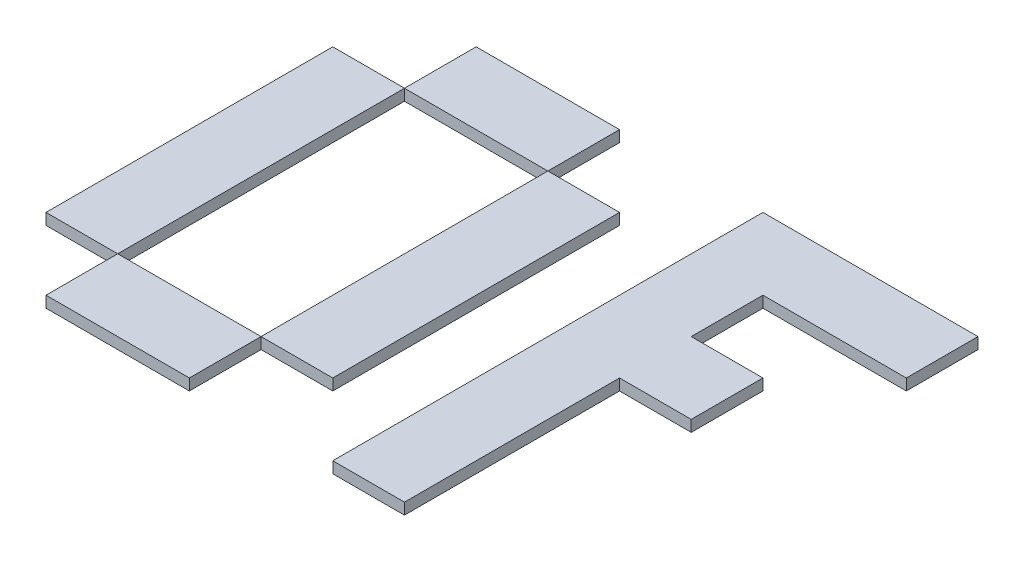
SolidWorks part; units mm, degrees
ref_plane "Front Plane" through (0, 0, 0) normal (0, 0, 1) x (1, 0, 0)
ref_plane "Top Plane" through (0, 0, 0) normal (0, 1, 0) x (1, 0, 0)
ref_plane "Right Plane" through (0, 0, 0) normal (1, 0, 0) x (0, 0, -1)
sketch "Sketch1" plane through (0, 0, 0) normal (0, 1, 0) x (1, 0, 0)
  line L1 (0, 0) -> (127, 0)
  line L2 (0, 0) -> (0, 203.2)
  line L3 (0, 203.2) -> (127, 203.2)
  line L4 (127, 0) -> (127, 203.2)
  dimension "D1" = 127
  dimension "D2" = 203.2
extrude "Boss-Extrude1" add sketch "Sketch1" along normal blind 2 contours L1 L4 L3 L2
sketch "Sketch2" plane through (0, 2, 0) normal (0, 1, 0) x (1, 0, 0)
  line L0 (0, 0) -> (0, 203.2) construction
  line L1 (12.7, 127) -> (25.4, 127)
  line L2 (12.7, 127) -> (12.7, 76.2)
  line L3 (12.7, 76.2) -> (25.4, 76.2)
  line L4 (25.4, 127) -> (25.4, 76.2)
  line L5 (0, 0) -> (127, 0) construction
  line L6 (88.9, 127) -> (88.9, 114.3)
  line L7 (25.4, 127) -> (50.8, 127)
  line L8 (25.4, 127) -> (25.4, 139.7)
  line L9 (25.4, 139.7) -> (50.8, 139.7)
  line L10 (50.8, 127) -> (50.8, 139.7)
  line L11 (25.4, 76.2) -> (50.8, 76.2)
  line L12 (25.4, 76.2) -> (25.4, 63.5)
  line L13 (25.4, 63.5) -> (50.8, 63.5)
  line L14 (50.8, 76.2) -> (50.8, 63.5)
  line L15 (50.8, 127) -> (63.5, 127)
  line L16 (50.8, 127) -> (50.8, 76.2)
  line L17 (50.8, 76.2) -> (63.5, 76.2)
  line L18 (63.5, 127) -> (63.5, 76.2)
  line L19 (76.2, 63.5) -> (88.9, 63.5)
  line L20 (76.2, 63.5) -> (76.2, 139.7)
  line L21 (76.2, 139.7) -> (88.9, 139.7)
  line L23 (88.9, 139.7) -> (114.3, 139.7)
  line L25 (88.9, 127) -> (114.3, 127)
  line L26 (114.3, 139.7) -> (114.3, 127)
  line L27 (88.9, 114.3) -> (101.6, 114.3)
  line L29 (88.9, 101.6) -> (101.6, 101.6)
  line L30 (101.6, 114.3) -> (101.6, 101.6)
  line L31 (88.9, 101.6) -> (88.9, 63.5)
  point P27 (95.25, 114.3)
  line M1 (0, 203.2) -> (0, 0)
  line M2 (0, 0) -> (127, 0)
  line M3 (127, 0) -> (127, 203.2)
  line M4 (127, 203.2) -> (0, 203.2)
  dimension "D1" = 12.7
  dimension "D2" = 50.8
  dimension "D3" = 76.2
  dimension "D4" = 12.7
  dimension "D5" = 25.4
  dimension "D6" = 12.7
  dimension "D7" = 12.7
  dimension "D8" = 12.7
  dimension "D9" = 76.2
  dimension "D10" = 12.7
  dimension "D11" = 12.7
  dimension "D12" = 25.4
  dimension "D13" = 12.7
  dimension "D14" = 12.7
  dimension "D15" = 12.7
extrude "Cut-Extrude9" cut sketch "Sketch2" against normal blind 2 contours L15 L18 L17 L14 L13 L12 L3 L2 L1 L8 L9 L10 L29 L31 L19 L20 L21 L23 L26 L25 L6 L27 L30 M4 M1 M2 M3
sketch "Sketch5" plane through (0, 2, 0) normal (0, 1, 0) x (1, 0, 0)
  line L1 (25.4, 127) -> (50.8, 127)
  line L2 (25.4, 127) -> (25.4, 76.2)
  line L3 (25.4, 76.2) -> (50.8, 76.2)
  line L4 (50.8, 127) -> (50.8, 76.2)
extrude "Cut-Extrude10" cut sketch "Sketch5" against normal blind 2
